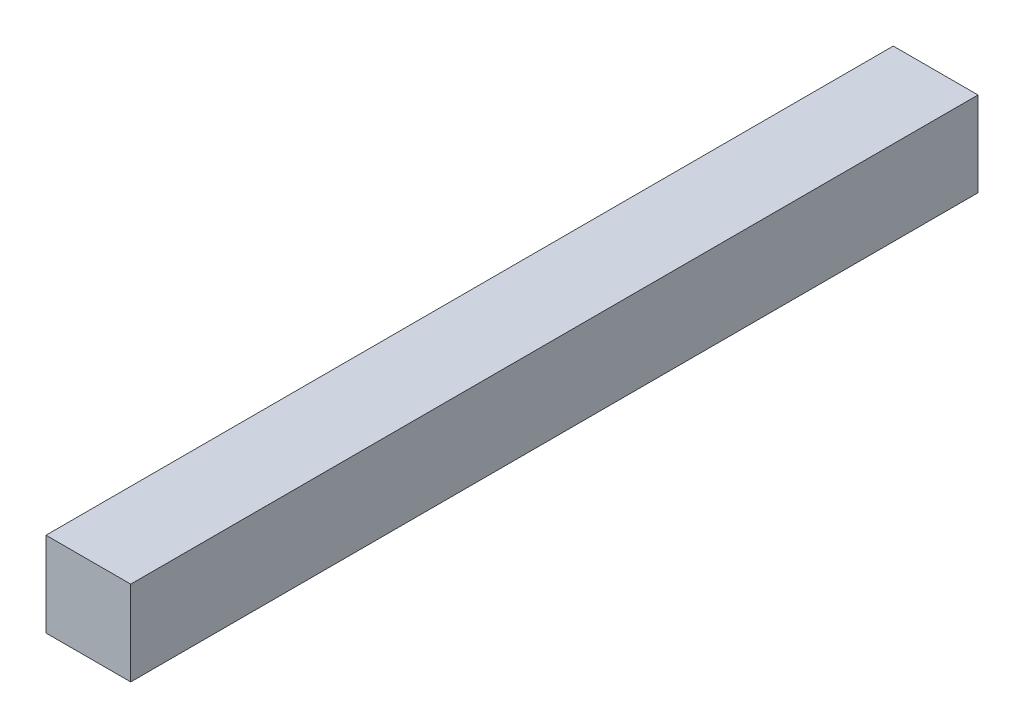
SolidWorks part; units mm, degrees
material "Brass"
ref_plane "Front Plane" through (0, 0, 0) normal (0, 0, 1) x (1, 0, 0)
ref_plane "Top Plane" through (0, 0, 0) normal (0, 1, 0) x (1, 0, 0)
ref_plane "Right Plane" through (0, 0, 0) normal (1, 0, 0) x (0, 0, -1)
sketch "Sketch1" plane through (0, 0, 0) normal (0, 0, 1) x (1, 0, 0)
  line L1 (3.175, -3.175) -> (-3.175, -3.175)
  line L2 (3.175, -3.175) -> (3.175, 3.175)
  line L3 (3.175, 3.175) -> (-3.175, 3.175)
  line L4 (-3.175, -3.175) -> (-3.175, 3.175)
  line L5 (3.175, -3.175) -> (-3.175, 3.175) construction
  line L6 (3.175, 3.175) -> (-3.175, -3.175) construction
  point P0 (0, 0)
  dimension "D1" = 6.35
  dimension "D2" = 6.35
extrude "Boss-Extrude1" add sketch "Sketch1" along normal mid plane 63.5
